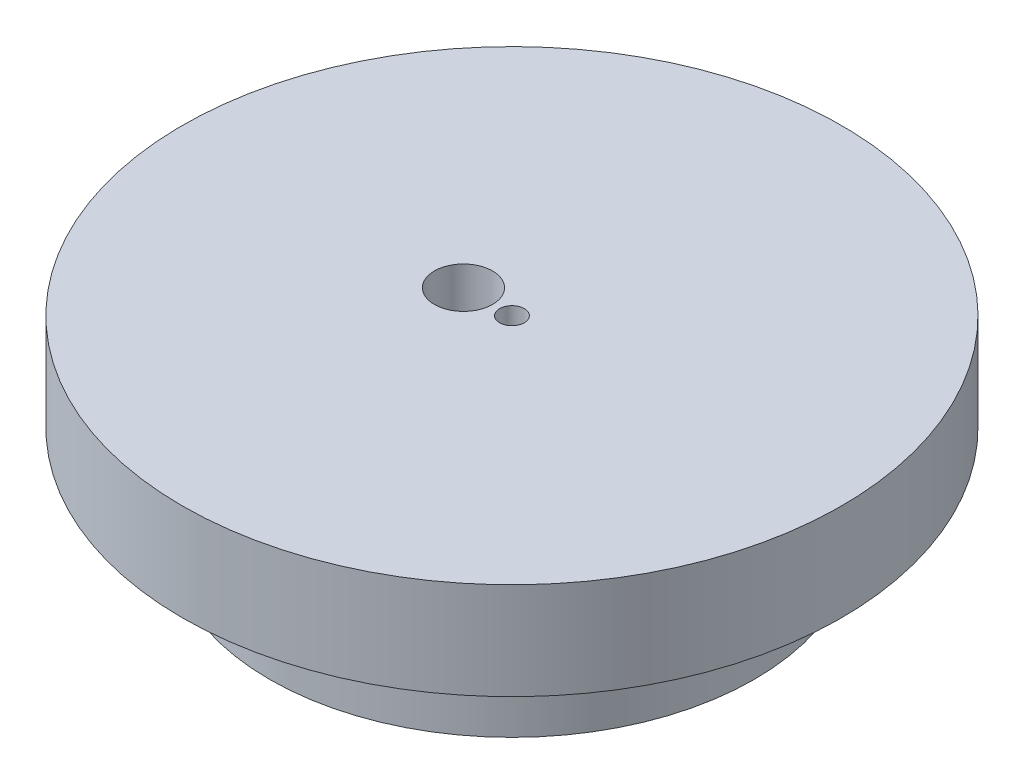
SolidWorks part; units mm, degrees
ref_plane "Front Plane" through (0, 0, 0) normal (0, 0, 1) x (1, 0, 0)
ref_plane "Top Plane" through (0, 0, 0) normal (0, 1, 0) x (1, 0, 0)
ref_plane "Right Plane" through (0, 0, 0) normal (1, 0, 0) x (0, 0, -1)
sketch "Sketch1" plane through (0, 0, 0) normal (0, 1, 0) x (1, 0, 0)
  line L39 (0, 8.5) -> (0, 11) construction
  line L40 (-1.5, 11) -> (1.5, 11)
  line L41 (-1.5, 11) -> (-2.4259, 8.1465)
  line L42 (1.5, 11) -> (2.4259, 8.1465)
  line L43 (6.7175, 8.8388) -> (4.045, 7.4758)
  line L44 (6.7175, 8.8388) -> (8.8388, 6.7175)
  line L45 (8.8388, 6.7175) -> (7.4758, 4.045)
  line L46 (11, 1.5) -> (8.1465, 2.4259)
  line L47 (11, 1.5) -> (11, -1.5)
  line L48 (11, -1.5) -> (8.1465, -2.4259)
  line L49 (8.8388, -6.7175) -> (7.4758, -4.045)
  line L50 (8.8388, -6.7175) -> (6.7175, -8.8388)
  line L51 (6.7175, -8.8388) -> (4.045, -7.4758)
  line L52 (1.5, -11) -> (2.4259, -8.1465)
  line L53 (1.5, -11) -> (-1.5, -11)
  line L54 (-1.5, -11) -> (-2.4259, -8.1465)
  line L55 (-6.7175, -8.8388) -> (-4.045, -7.4758)
  line L56 (-6.7175, -8.8388) -> (-8.8388, -6.7175)
  line L57 (-8.8388, -6.7175) -> (-7.4758, -4.045)
  line L58 (-11, -1.5) -> (-8.1465, -2.4259)
  line L59 (-11, -1.5) -> (-11, 1.5)
  line L60 (-11, 1.5) -> (-8.1465, 2.4259)
  line L61 (-8.8388, 6.7175) -> (-7.4758, 4.045)
  line L62 (-8.8388, 6.7175) -> (-6.7175, 8.8388)
  line L63 (-6.7175, 8.8388) -> (-4.045, 7.4758)
  circle A14 centre (0, 0) radius 8.5 construction
  arc A15 (2.4259, 8.1465) -> (4.045, 7.4758) centre (0, 0) cw
  arc A16 (7.4758, 4.045) -> (8.1465, 2.4259) centre (0, 0) cw
  arc A17 (8.1465, -2.4259) -> (7.4758, -4.045) centre (0, 0) cw
  arc A18 (4.045, -7.4758) -> (2.4259, -8.1465) centre (0, 0) cw
  arc A19 (-2.4259, -8.1465) -> (-4.045, -7.4758) centre (0, 0) cw
  arc A20 (-7.4758, -4.045) -> (-8.1465, -2.4259) centre (0, 0) cw
  arc A21 (-8.1465, 2.4259) -> (-7.4758, 4.045) centre (0, 0) cw
  arc A22 (-4.045, 7.4758) -> (-2.4259, 8.1465) centre (0, 0) cw
  circle A23 centre (0, 0) radius 25
  point P31 (0, 0)
  point P71 (0, 11)
  point P105 (0, 0)
  dimension "D1" = 50
  dimension "D5" = 17
  dimension "D6" = 2.5
  dimension "D7" = 3
  dimension "D8" = 3
  dimension "D9" = 8
extrude "Boss-Extrude1" add sketch "Sketch1" along normal blind 10
sketch "Sketch2" plane through (0, 10, 0) normal (0, 1, 0) x (1, 0, 0)
  circle A0 centre (0, 0) radius 1.27
  circle A1 centre (0, 0) radius 34
  dimension "D1" = 2.54
  dimension "D2" = 68
extrude "Boss-Extrude2" add sketch "Sketch2" along normal blind 10
sketch "Sketch3" plane through (0, 20, 0) normal (0, 1, 0) x (1, 0, 0)
  circle A0 centre (-5, 0) radius 3
  dimension "D2" = 6
  dimension "D1" = 5
extrude "Cut-Extrude1" cut sketch "Sketch3" against normal through all
sketch "Sketch4" plane through (0, 0, 0) normal (0, -1, 0) x (-1, 0, 0)
  text T0 "17"
extrude "Cut-Extrude2" cut sketch "Sketch4" against normal blind 2.5
